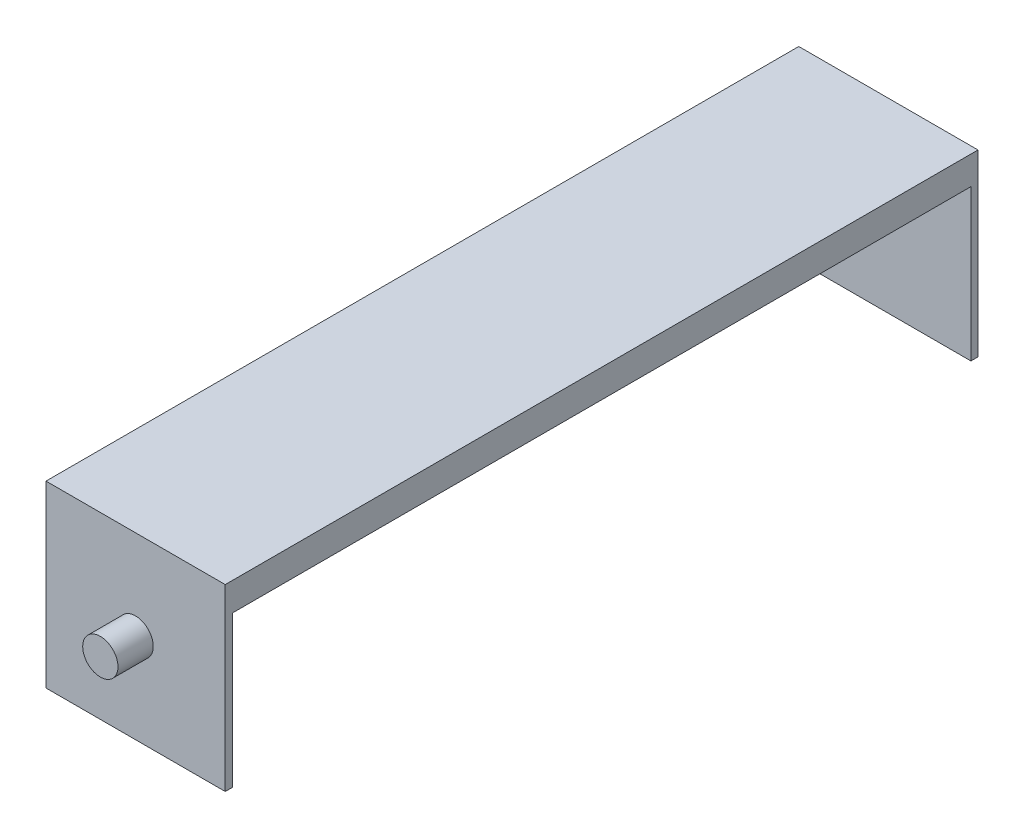
SolidWorks part; units mm, degrees
ref_plane "Front Plane" through (0, 0, 0) normal (0, 0, 1) x (1, 0, 0)
ref_plane "Top Plane" through (0, 0, 0) normal (0, 1, 0) x (1, 0, 0)
ref_plane "Right Plane" through (0, 0, 0) normal (1, 0, 0) x (0, 0, -1)
sketch "Sketch1" plane through (0, 0, 0) normal (0, 0, 1) x (1, 0, 0)
  line L1 (-127, -127) -> (127, -127)
  line L2 (-127, -127) -> (-127, 127)
  line L3 (-127, 127) -> (127, 127)
  line L4 (127, -127) -> (127, 127)
  line L5 (-127, -127) -> (127, 127) construction
  line L6 (-127, 127) -> (127, -127) construction
  point P0 (0, 0)
  dimension "D1" = 254
  dimension "D2" = 254
extrude "Boss-Extrude1" add sketch "Sketch1" along normal mid plane 1066.8
sketch "Sketch2" plane through (0, 0, 533.4) normal (0, 0, 1) x (1, 0, 0)
  circle A0 centre (0, 0) radius 25
  dimension "D1" = 50
extrude "Boss-Extrude2" add sketch "Sketch2" along normal blind 50
mirror "Mirror1" about plane through (0, 0, 0) normal (0, 0, 1) of "Boss-Extrude2"
sketch "Sketch3" plane through (127, 0, 0) normal (1, 0, 0) x (0, 0, -1)
  line L0 (-533.4, -127) -> (-533.4, 127) construction
  line L1 (-523.4, 87) -> (523.4, 87)
  line L2 (-523.4, 87) -> (-523.4, -180.6398)
  line L3 (-523.4, -180.6398) -> (523.4, -180.6398)
  line L4 (523.4, 87) -> (523.4, -180.6398)
  line L5 (-523.4, 87) -> (523.4, -180.6398) construction
  line L6 (-523.4, -180.6398) -> (523.4, 87) construction
  line L7 (533.4, -127) -> (533.4, 127) construction
  line L8 (-533.4, 127) -> (533.4, 127) construction
  point P0 (0, -46.8199)
  dimension "D1" = 10
  dimension "D2" = 10
  dimension "D3" = 40
extrude "Cut-Extrude1" cut sketch "Sketch3" against normal up to surface (254 mm away) up to face at (-127, 0, 0)
